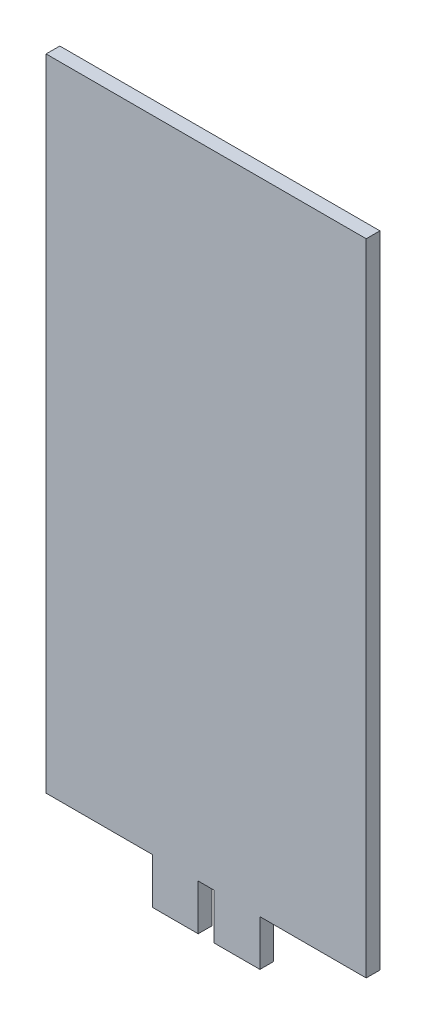
SolidWorks part; units mm, degrees
material "Glas"
ref_plane "Ebene vorne" through (0, 0, 0) normal (0, 0, 1) x (1, 0, 0)
ref_plane "Ebene oben" through (0, 0, 0) normal (0, 1, 0) x (1, 0, 0)
ref_plane "Ebene rechts" through (0, 0, 0) normal (1, 0, 0) x (0, 0, -1)
sketch "Skizze1" plane through (0, 0, 0) normal (0, 0, 1) x (1, 0, 0)
  line L1 (0, 0) -> (35, 0)
  line L2 (0, 0) -> (0, 75)
  line L3 (0, 75) -> (35, 75)
  line L4 (35, 0) -> (35, 75)
  dimension "D1" = 35
  dimension "D2" = 75
extrude "Aufsatz-Linear austragen1" add sketch "Skizze1" along normal blind 1.5
sketch "Skizze2" plane through (0, 0, 1.5) normal (0, 0, 1) x (1, 0, 0)
  line L0 (0, 0) -> (35, 0) construction
  line L1 (0, 0) -> (11.63, 0)
  line L2 (0, 0) -> (0, 5)
  line L3 (0, 5) -> (11.63, 5)
  line L4 (11.63, 0) -> (11.63, 5)
  line L5 (23.38, 5) -> (35, 5)
  line L6 (23.38, 5) -> (23.38, 0)
  line L7 (23.38, 0) -> (35, 0)
  line L8 (35, 5) -> (35, 0)
  line L9 (16.63, 0) -> (18.38, 0)
  line L10 (16.63, 0) -> (16.63, 5)
  line L11 (16.63, 5) -> (18.38, 5)
  line L12 (18.38, 0) -> (18.38, 5)
  dimension "D1" = 5
  dimension "D2" = 5
  dimension "D3" = 5
  dimension "D4" = 11.63
  dimension "D5" = 1.75
  dimension "D6" = 5
extrude "Schnitt-Linear austragen1" cut sketch "Skizze2" against normal blind 1.5
